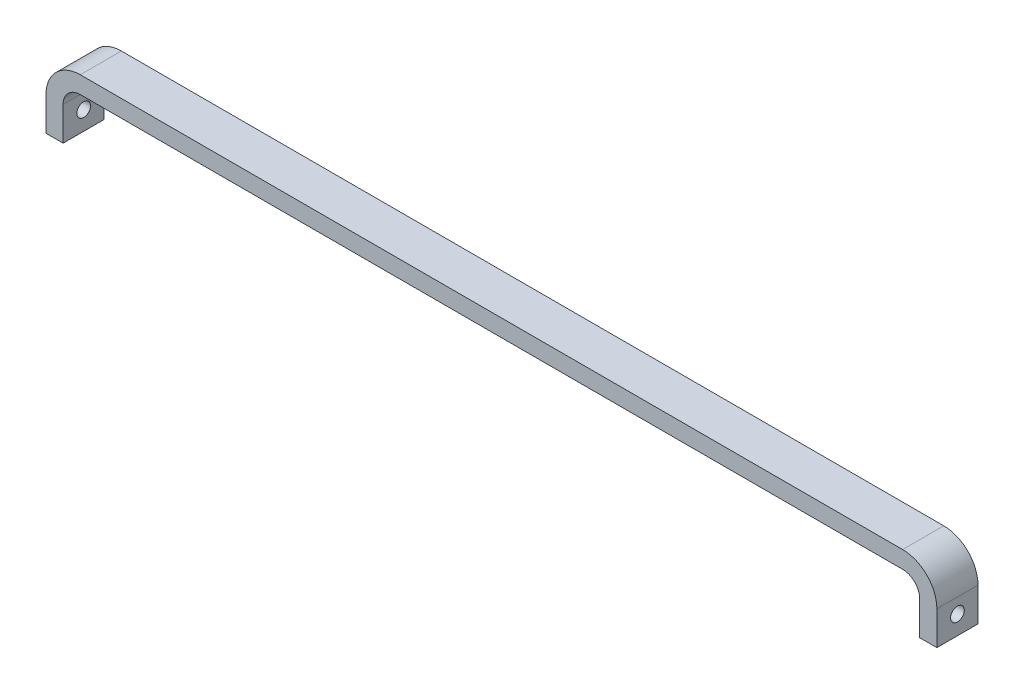
SolidWorks part; units mm, degrees
ref_plane "Front Plane" through (0, 0, 0) normal (0, 0, 1) x (1, 0, 0)
ref_plane "Top Plane" through (0, 0, 0) normal (0, 1, 0) x (1, 0, 0)
ref_plane "Right Plane" through (0, 0, 0) normal (1, 0, 0) x (0, 0, -1)
sketch "Sketch1" plane through (0, 0, 0) normal (0, 0, 1) x (1, 0, 0)
  line L0 (0, 0) -> (0, 19.6)
  line L3 (0, 19.6) -> (20, 19.6) construction
  line L4 (20, 19.6) -> (20, 39.6) construction
  line L5 (0, 0) -> (10, 0)
  line L6 (260, 0) -> (260, 41.1401) construction
  line L7 (20, 39.6) -> (500, 39.6)
  line L8 (520, 0) -> (520, 19.6)
  line L9 (0, 0) -> (10, 0)
  line L10 (20, 29.6) -> (500, 29.6)
  line L12 (10, 19.6) -> (10, 0)
  line L13 (510, 19.6) -> (510, 0)
  line L14 (510, 0) -> (520, 0)
  arc A2 (20, 39.6) -> (0, 19.6) centre (20, 19.6) ccw
  arc A3 (500, 39.6) -> (520, 19.6) centre (500, 19.6) cw
  arc A4 (20, 29.6) -> (10, 19.6) centre (20, 19.6) ccw
  arc A5 (500, 29.6) -> (510, 19.6) centre (500, 19.6) cw
  point P15 (260, 39.6)
  point P19 (260, 29.6)
  dimension "D1" = 19.6
  dimension "D2" = 20
  dimension "D4" = 520
extrude "Boss-Extrude2" add sketch "Sketch1" along normal blind 24 contours L10 A5 L13 L14 L8 A3 L7 A2 L0 L5 L12 A4
sketch "Sketch2" plane through (0, 0, 0) normal (-1, 0, 0) x (0, 0, 1)
  line L1 (24, 0) -> (0, 0) construction
  circle A0 centre (12, 11) radius 4
  dimension "D1" = 11
extrude "Cut-Extrude1" cut sketch "Sketch2" against normal through all
